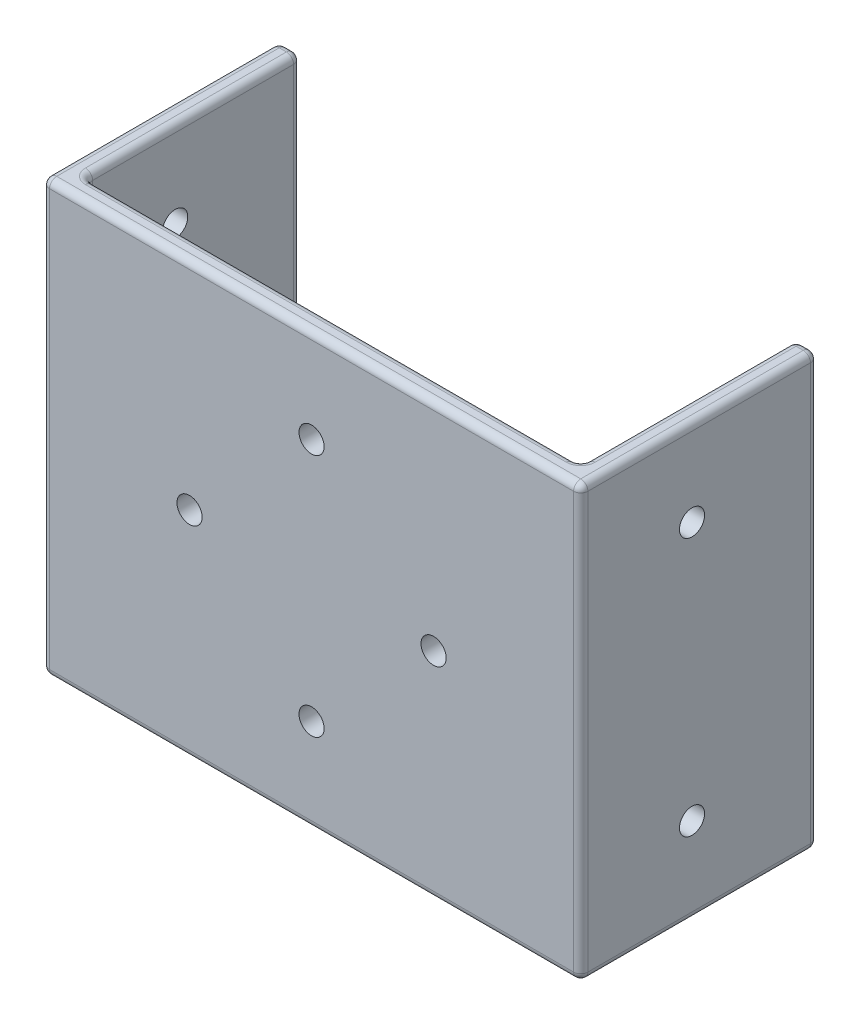
SolidWorks part; units mm, degrees
ref_plane "Front Plane" through (0, 0, 0) normal (0, 0, 1) x (1, 0, 0)
ref_plane "Top Plane" through (0, 0, 0) normal (0, 1, 0) x (1, 0, 0)
ref_plane "Right Plane" through (0, 0, 0) normal (1, 0, 0) x (0, 0, -1)
sketch "Sketch1" plane through (0, 0, 0) normal (0, 0, 1) x (1, 0, 0)
  line L1 (-37.5, -30) -> (37.5, -30)
  line L2 (-37.5, -30) -> (-37.5, 30)
  line L3 (-37.5, 30) -> (37.5, 30)
  line L4 (37.5, -30) -> (37.5, 30)
  line L5 (-37.5, -30) -> (37.5, 30) construction
  line L6 (-37.5, 30) -> (37.5, -30) construction
  point P0 (0, 0)
  dimension "D1" = 60
  dimension "D2" = 75
extrude "Boss-Extrude1" add sketch "Sketch1" along normal blind 3
sketch "Sketch2" plane through (0, 0, 0) normal (0, 0, -1) x (-1, 0, 0)
  line L0 (37.5, -30) -> (-37.5, -30) construction
  line L1 (-37.5, 30) -> (-34.5, 30)
  line L2 (-37.5, 30) -> (-37.5, -30)
  line L3 (-37.5, -30) -> (-34.5, -30)
  line L4 (-34.5, 30) -> (-34.5, -30)
  dimension "D1" = 3
extrude "Boss-Extrude2" add sketch "Sketch2" along normal blind 30
mirror "Mirror1" about plane through (0, 0, 0) normal (1, 0, 0) of "Boss-Extrude2"
sketch "Sketch3" plane through (0, 0, 3) normal (0, 0, 1) x (1, 0, 0)
  circle A0 centre (0, 17) radius 1.75
  circle A4 centre (17, 0) radius 1.75
  circle A5 centre (0, -17) radius 1.75
  circle A6 centre (-17, 0) radius 1.75
  point P12 (0, 0)
  dimension "D1" = 3.5
  dimension "D2" = 17
  dimension "D3" = 4
extrude "Cut-Extrude1" cut sketch "Sketch3" against normal blind 30
fillet "Fillet1" radius 1 24 edges at (-34.5, 0, 0) (0, 30, 0) (-34.5, -30, -15) (-34.5, 30, -15) (34.5, 0, 0) (0, -30, 0) (-34.5, 0, -30) (34.5, 30, -15) (-36, 30, -30) (-36, -30, -30) (34.5, 0, -30) (34.5, -30, -15) (-37.5, 0, -30) (36, 30, -30) (-37.5, 30, -13.5) (37.5, 0, -30) (36, -30, -30) (-37.5, -30, -13.5) (-37.5, 0, 3) (37.5, 30, -13.5) (0, 30, 3) (37.5, -30, -13.5) (0, -30, 3) (37.5, 0, 3)
sketch "Sketch4" plane through (37.5, 0, 0) normal (1, 0, 0) x (0, 0, -1)
  line L0 (-2, -29) -> (29, -29) construction
  line L1 (29, 29) -> (-2, 29) construction
  circle A0 centre (12.5, 18) radius 1.75
  circle A1 centre (12.5, -18) radius 1.75
  point P4 (0, 0)
  dimension "D1" = 3.5
  dimension "D2" = 3.5
  dimension "D3" = 11
  dimension "D4" = 11
  dimension "D5" = 12.5
extrude "Cut-Extrude2" cut sketch "Sketch4" against normal through all
